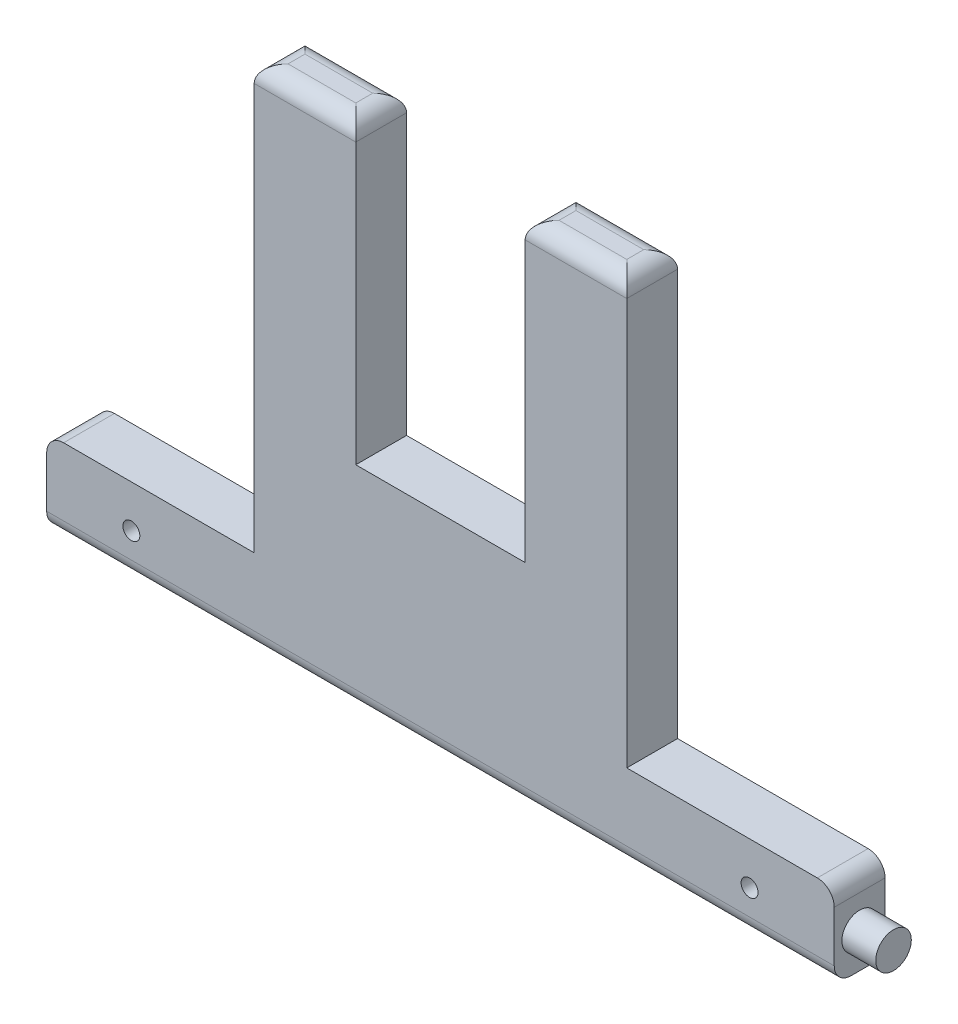
SolidWorks part; units mm, degrees
ref_plane "Front Plane" through (0, 0, 0) normal (0, 0, 1) x (1, 0, 0)
ref_plane "Top Plane" through (0, 0, 0) normal (0, 1, 0) x (1, 0, 0)
ref_plane "Right Plane" through (0, 0, 0) normal (1, 0, 0) x (0, 0, -1)
sketch "Sketch1" plane through (0, 0, 0) normal (0, 0, 1) x (1, 0, 0)
  line L0 (-55.1749, -67.4702) -> (-55.1749, -54.7702)
  line L1 (-55.1749, -67.4702) -> (62.9351, -67.4702)
  line L5 (-55.1749, -54.7702) -> (-24.0599, -54.7702)
  line L6 (-24.0599, -54.7702) -> (-24.0599, 8.7298)
  line L7 (-24.0599, 8.7298) -> (-8.8199, 8.7298)
  line L8 (-8.8199, 8.7298) -> (-8.8199, -35.7202)
  line L9 (-8.8199, -35.7202) -> (16.5801, -35.7202)
  line L10 (16.5801, -35.7202) -> (16.5801, 8.7298)
  line L11 (16.5801, 8.7298) -> (31.8201, 8.7298)
  line L12 (31.8201, 8.7298) -> (31.8201, -54.7702)
  line L13 (31.8201, -54.7702) -> (62.9351, -54.7702)
  line L14 (62.9351, -54.7702) -> (62.9351, -67.4702)
  circle A0 centre (-42.4749, -61.1202) radius 1.27
  circle A1 centre (50.2351, -61.1202) radius 1.27
  point P0 (0, 0)
  point P1 (62.9351, -61.1202)
  dimension "D11" = 6.35
  dimension "D12" = 118.11
  dimension "D1" = 44.45
  dimension "D2" = 44.45
  dimension "D3" = 12.7
  dimension "D4" = 12.7
  dimension "D5" = 31.115
  dimension "D6" = 12.7
  dimension "D7" = 15.24
  dimension "D8" = 15.24
  dimension "D9" = 25.4
  dimension "D10" = 63.5
  dimension "D13" = 12.7
  dimension "D14" = 31.115
extrude "Boss-Extrude1" add sketch "Sketch1" along normal blind 7.62
sketch "Sketch3" plane through (0, -35.7202, 0) normal (0, 1, 0) x (1, 0, 0)
  line L0 (3.8801, 0) -> (3.8801, -7.62) construction
  line L1 (16.5801, 0) -> (-8.8199, 0) construction
  line L2 (16.5801, -7.62) -> (-8.8199, -7.62) construction
fillet "Fillet1" radius 2.54 8 edges at (24.2001, 8.7298, 7.62) (24.2001, 8.7298, 0) (-16.4399, 8.7298, 7.62) (-16.4399, 8.7298, 0) (31.8201, 8.7298, 3.81) (16.5801, 8.7298, 3.81) (-8.8199, 8.7298, 3.81) (-24.0599, 8.7298, 3.81)
fillet "Fillet2" radius 2.54 2 edges at (3.8801, -67.4702, 7.62) (3.8801, -67.4702, 0)
fillet "Fillet3" radius 2.54 2 edges at (62.9351, -54.7702, 3.81) (-55.1749, -54.7702, 3.81)
sketch "Sketch4" plane through (62.9351, 0, 0) normal (1, 0, 0) x (0, 0, -1)
  circle A0 centre (-3.81, -62.2504) radius 2.667
extrude "Boss-Extrude2" add sketch "Sketch4" along normal blind 5.08
sketch "Sketch5" plane through (-55.1749, 0, 0) normal (-1, 0, 0) x (0, 0, 1)
  line L1 (1.9275, -59.9234) -> (5.6105, -59.9234)
  line L2 (1.9275, -59.9234) -> (1.9275, -65.3844)
  line L3 (1.9275, -65.3844) -> (5.6105, -65.3844)
  line L4 (5.6105, -59.9234) -> (5.6105, -65.3844)
  dimension "D1" = 5.461
  dimension "D2" = 3.683
extrude "Cut-Extrude2" cut sketch "Sketch5" against normal blind 8.89
